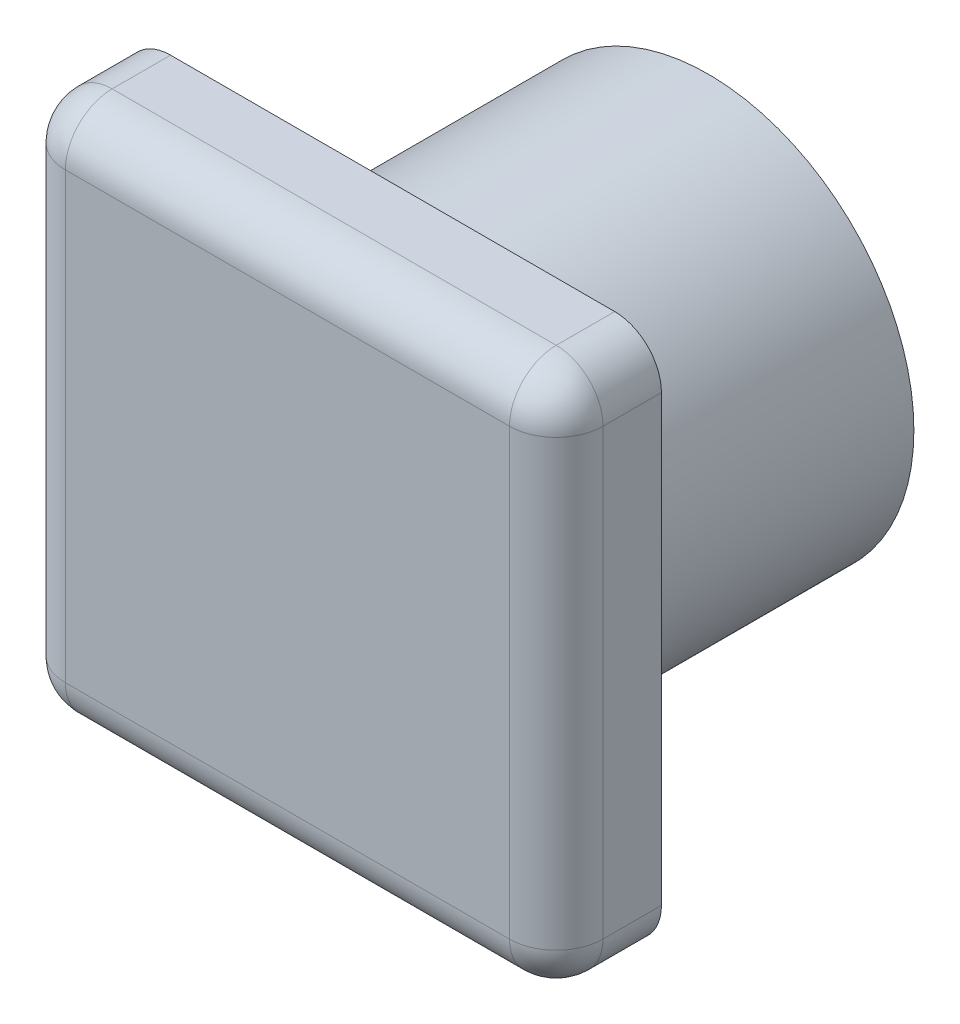
SolidWorks part; units mm, degrees
ref_plane "Front Plane" through (0, 0, 0) normal (0, 0, 1) x (1, 0, 0)
ref_plane "Top Plane" through (0, 0, 0) normal (0, 1, 0) x (1, 0, 0)
ref_plane "Right Plane" through (0, 0, 0) normal (1, 0, 0) x (0, 0, -1)
sketch "Sketch3" plane through (0, 0, 0) normal (0, 0, 1) x (1, 0, 0)
  circle A0 centre (0, 0) radius 8.8
  dimension "D1" = 17.6
extrude "Boss-Extrude1" add sketch "Sketch3" along normal blind 13.5
sketch "Sketch4" plane through (0, 0, 13.5) normal (0, 0, 1) x (1, 0, 0)
  line L1 (-11.5, -11.5) -> (11.5, -11.5)
  line L2 (-11.5, -11.5) -> (-11.5, 11.5)
  line L3 (-11.5, 11.5) -> (11.5, 11.5)
  line L4 (11.5, -11.5) -> (11.5, 11.5)
  line L5 (-11.5, -11.5) -> (11.5, 11.5) construction
  line L6 (-11.5, 11.5) -> (11.5, -11.5) construction
  point P0 (0, 0)
  dimension "D1" = 23
  dimension "D2" = 23
extrude "Boss-Extrude2" add sketch "Sketch4" along normal blind 4.5
fillet "Fillet1" radius 2 8 edges at (0, -11.5, 18) (-11.5, 0, 18) (0, 11.5, 18) (11.5, 0, 18) (11.5, -11.5, 15.75) (-11.5, 11.5, 15.75) (-11.5, -11.5, 15.75) (11.5, 11.5, 15.75)
